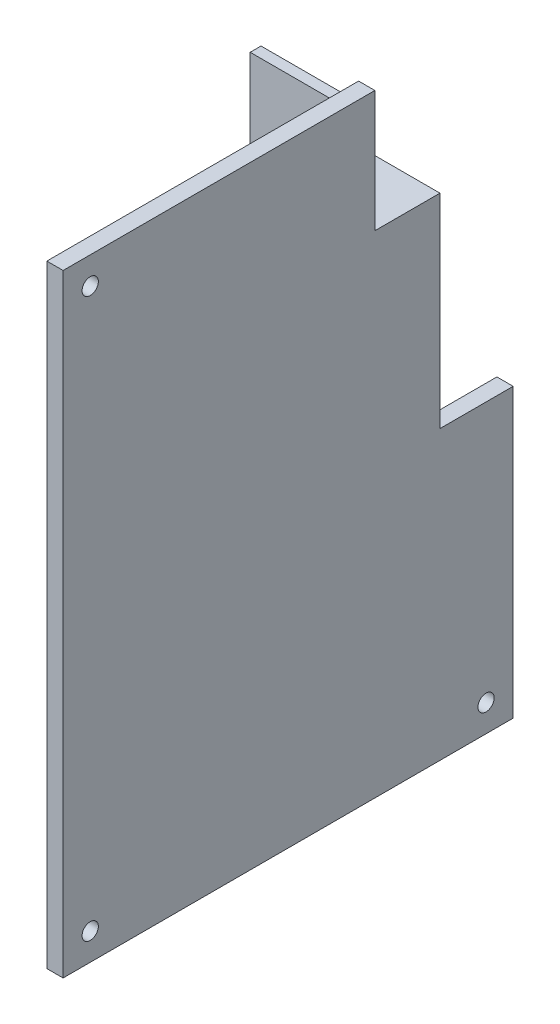
SolidWorks part; units mm, degrees
ref_plane "Ön Düzlem" through (0, 0, 0) normal (1, 0, 0) x (0, 1, 0)
ref_plane "Üst Düzlem" through (0, 0, 0) normal (0, 0, 1) x (0, 1, 0)
ref_plane "Sağ Düzlem" through (0, 0, 0) normal (0, 1, 0) x (-1, 0, 0)
sketch "Sketch1" plane through (0, 0, 0) normal (1, 0, 0) x (0, 1, 0)
  line L39 (-9.0543, -23.3949) -> (28.5461, -23.3949)
  line L40 (28.5461, -23.3949) -> (28.5461, -13.3949)
  line L41 (28.5461, -13.3949) -> (47.9457, -13.3949)
  line L110 (47.9457, -13.3949) -> (50.9457, -13.3949)
  line L111 (50.9457, -13.3949) -> (50.9457, 44.1051)
  line L112 (50.9457, 44.1051) -> (-62.0543, 44.1051)
  line L113 (-62.0543, 44.1051) -> (-62.0543, -38.8949)
  line L114 (-62.0543, -38.8949) -> (-9.0543, -38.8949)
  line L115 (-9.0543, -38.8949) -> (-9.0543, -23.3949)
  circle A0 centre (-57.0543, -33.8949) radius 1.5
  circle A1 centre (-57.0543, 39.1051) radius 1.5
  circle A2 centre (45.9457, 39.1051) radius 1.5
extrude "Boss-Extrude1" add sketch "Sketch1" along normal blind 3
sketch "Sketch2" plane through (0, 0, 0) normal (-1, 0, 0) x (0, -1, 0)
  line L0 (9.0543, -23.3949) -> (9.0543, -25.3949)
  line L2 (9.0543, -38.8949) -> (9.0543, -23.3949) construction
  line L3 (-28.5461, -23.3949) -> (-28.5461, -25.3949)
  line L4 (-28.5461, -25.3949) -> (9.0543, -25.3949)
  line L5 (-28.5461, -23.3949) -> (-28.5461, -13.3949)
  line L6 (-28.5461, -13.3949) -> (-47.5457, -13.3949)
  line L9 (9.0543, -23.3949) -> (-26.5457, -23.3949)
  line L10 (9.0543, -23.3949) -> (-28.5461, -23.3949) construction
  line L11 (-26.5457, -23.3949) -> (-26.5457, -11.3949)
  line L12 (-26.5457, -11.3949) -> (-47.5457, -11.3949)
  line L19 (-47.5457, -13.3949) -> (-47.5457, -11.3949)
extrude "Boss-Extrude2" add sketch "Sketch2" along normal blind 18 and the other way up to surface other way up to face at (3, 2.0958, -7.8949)
